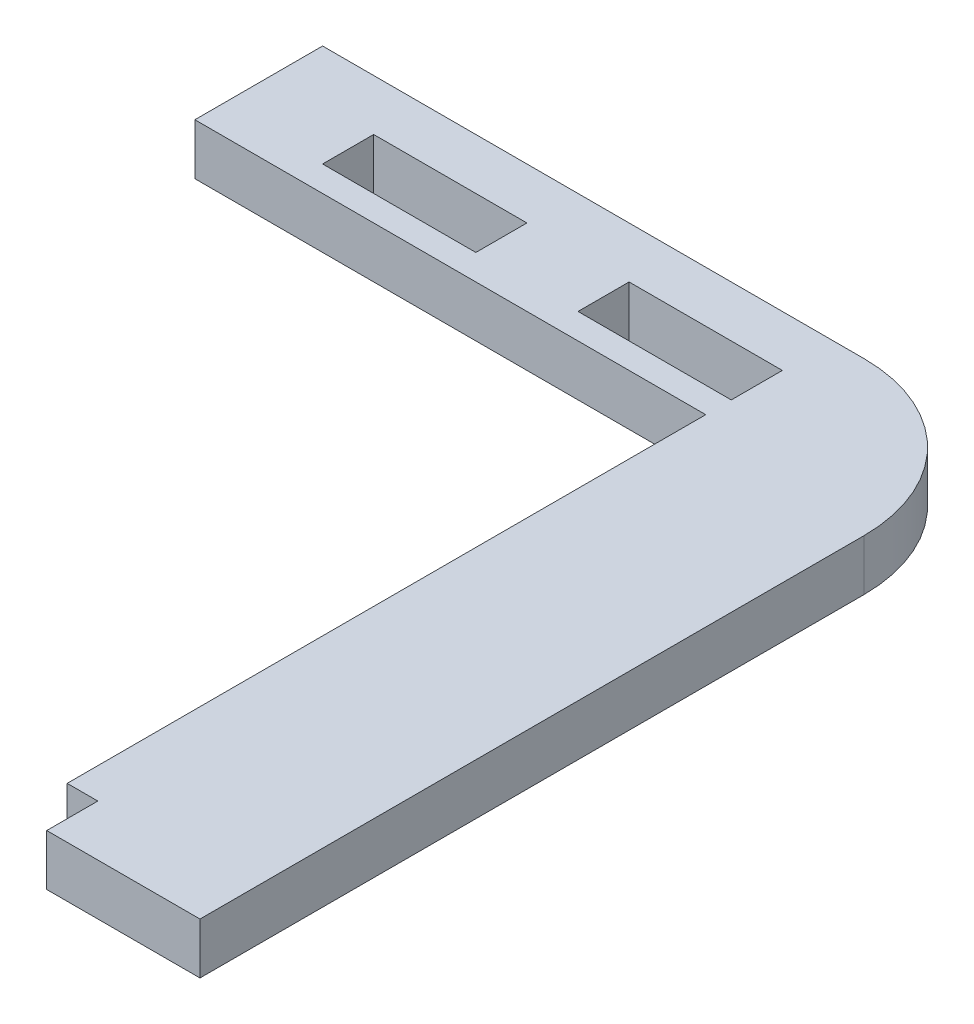
SolidWorks part; units mm, degrees
ref_plane "Front Plane" through (0, 0, 0) normal (0, 0, 1) x (1, 0, 0)
ref_plane "Top Plane" through (0, 0, 0) normal (0, 1, 0) x (1, 0, 0)
ref_plane "Right Plane" through (0, 0, 0) normal (1, 0, 0) x (0, 0, -1)
sketch "Sketch1" plane through (0, 0, 0) normal (0, 1, 0) x (1, 0, 0)
  line L0 (-34, -25) -> (-37, -25)
  line L4 (-37, -25) -> (-37, 37.5)
  line L6 (-34, -25) -> (-34, -30)
  line L7 (-34, -30) -> (-19, -30)
  line L9 (-19, 50) -> (-87, 50)
  line L11 (-37, 37.5) -> (-87, 37.5)
  line L12 (-87, 50) -> (-87, 37.5)
  line L13 (-77, 40) -> (-62, 40)
  line L14 (-77, 40) -> (-77, 45)
  line L15 (-77, 45) -> (-62, 45)
  line L16 (-62, 40) -> (-62, 45)
  line L17 (-19, 50) -> (-19, -30)
  line L19 (-52, 40) -> (-37, 40)
  line L20 (-52, 40) -> (-52, 45)
  line L21 (-52, 45) -> (-37, 45)
  line L22 (-37, 40) -> (-37, 45)
  point P12 (-87, 43.75)
  point P17 (-52, 42.5)
  dimension "D2" = 3
  dimension "D3" = 15
  dimension "D4" = 62.5
  dimension "D5" = 12.5
  dimension "D6" = 50
  dimension "D7" = 10
  dimension "D8" = 2.5
  dimension "D9" = 5
  dimension "D10" = 15
  dimension "D11" = 5
  dimension "D12" = 10
  dimension "D13" = 15
extrude "Boss-Extrude1" add sketch "Sketch1" along normal blind 5
fillet "Fillet3" radius 15 1 edges at (-19, 2.5, -50)
